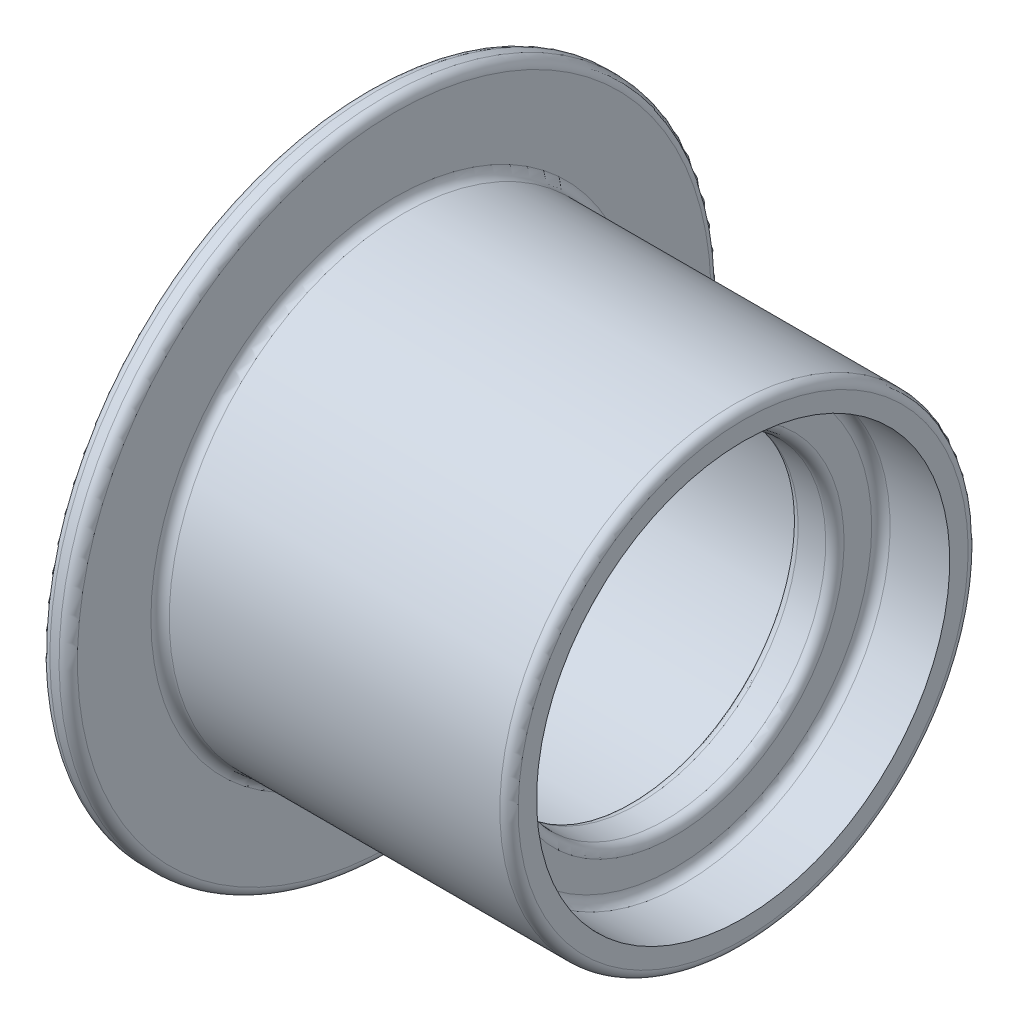
SolidWorks part; units mm, degrees
ref_plane "Front Plane" through (0, 0, 0) normal (0, 0, 1) x (1, 0, 0)
ref_plane "Top Plane" through (0, 0, 0) normal (0, 1, 0) x (1, 0, 0)
ref_plane "Right Plane" through (0, 0, 0) normal (1, 0, 0) x (0, 0, -1)
sketch "Sketch2" plane through (0, 0, 0) normal (0, 0, 1) x (1, 0, 0)
  line L0 (1, 0) -> (37, 0)
  line L1 (0, 1) -> (0, 9)
  line L2 (-1, 10) -> (-2, 10)
  line L3 (-3, 9) -> (-3, -2)
  line L11 (38, -3) -> (38, -1)
  line L12 (-2, -3) -> (6, -3)
  line L13 (7, -4) -> (7, -4.5073)
  line L14 (8, -5.5073) -> (24.5, -5.5073)
  line L15 (25.5, -6.5073) -> (25.5, -7.0073)
  line L16 (26.5, -8.0073) -> (29.5, -8.0073)
  line L17 (7, -3) -> (7, -25.5) construction
  line L18 (30.5, -7.0073) -> (30.5, -4)
  line L19 (31.5, -3) -> (38, -3)
  line L20 (7, -25.5) -> (-19.5564, -25.5) construction
  arc A0 (-2, 10) -> (-3, 9) centre (-2, 9) ccw
  arc A1 (-1, 10) -> (0, 9) centre (-1, 9) cw
  arc A2 (1, 0) -> (0, 1) centre (1, 1) cw
  arc A3 (-2, -3) -> (-3, -2) centre (-2, -2) cw
  arc A4 (38, -1) -> (37, 0) centre (37, -1) ccw
  arc A5 (29.5, -8.0073) -> (30.5, -7.0073) centre (29.5, -7.0073) ccw
  arc A6 (7, -4) -> (6, -3) centre (6, -4) ccw
  arc A7 (8, -5.5073) -> (7, -4.5073) centre (8, -4.5073) cw
  arc A8 (26.5, -8.0073) -> (25.5, -7.0073) centre (26.5, -7.0073) cw
  arc A9 (31.5, -3) -> (30.5, -4) centre (31.5, -4) ccw
  arc A10 (25.5, -6.5073) -> (24.5, -5.5073) centre (24.5, -6.5073) ccw
  point P17 (-3, 10)
  point P20 (0, 10)
  point P23 (0, 0)
  point P26 (-3, -3)
  point P27 (38, 0)
  point P33 (30.5, -8.0073)
  point P39 (7, -5.5073)
  point P42 (25.5, -8.0073)
  point P45 (30.5, -3)
  point P48 (25.5, -5.5073)
  dimension "D6" = 1
  dimension "D7" = 1
  dimension "D13" = 1
  dimension "D15" = 1
  dimension "D16" = 1
  dimension "D17" = 1
  dimension "D1" = 3
  dimension "D2" = 38
  dimension "D3" = 3
  dimension "D4" = 10
  dimension "D5" = 3
  dimension "D8" = 9
  dimension "D9" = 7.5
  dimension "D10" = 5
  dimension "D11" = 2.5
  dimension "D12" = 5.5073
  dimension "D14" = 22.5
revolve "Revolve1" add sketch "Sketch2" angle 360 about L20
